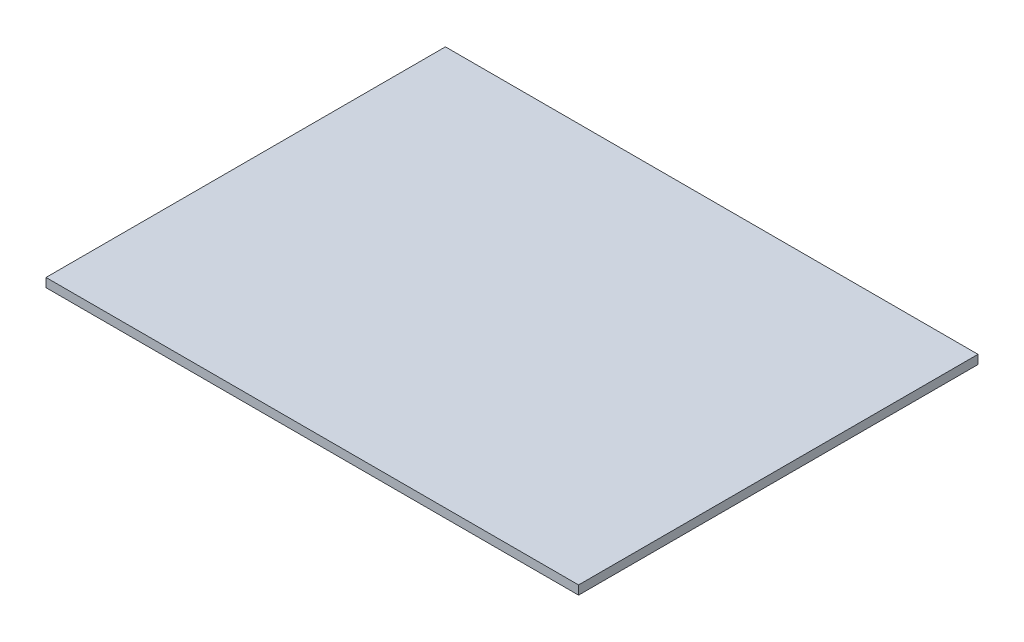
SolidWorks part; units mm, degrees
ref_plane "前视基准面" through (0, 0, 0) normal (0, 0, 1) x (1, 0, 0)
ref_plane "上视基准面" through (0, 0, 0) normal (0, 1, 0) x (1, 0, 0)
ref_plane "右视基准面" through (0, 0, 0) normal (1, 0, 0) x (0, 0, -1)
sketch "草图1" plane through (0, 0, 0) normal (0, 1, 0) x (1, 0, 0)
  line L1 (-60, 45) -> (60, 45)
  line L2 (-60, 45) -> (-60, -45)
  line L3 (-60, -45) -> (60, -45)
  line L4 (60, 45) -> (60, -45)
  line L5 (0, -45) -> (0, 45) construction
  line L6 (-60, 0) -> (60, 0) construction
  point P0 (0, 0)
  dimension "D1" = 90
  dimension "D2" = 120
extrude "凸台-拉伸1" add sketch "草图1" along normal blind 2
